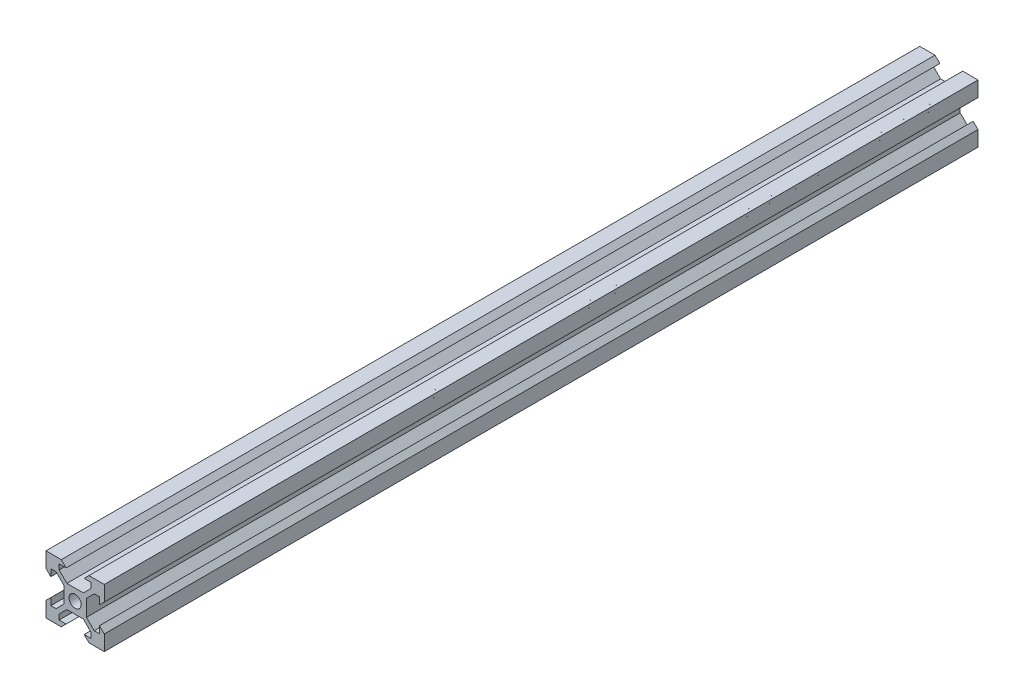
SolidWorks part; units mm, degrees
material "6061-T6 (SS)"
ref_plane "Front Plane" through (0, 0, 0) normal (0, 0, 1) x (1, 0, 0)
ref_plane "Top Plane" through (0, 0, 0) normal (0, 1, 0) x (1, 0, 0)
ref_plane "Right Plane" through (0, 0, 0) normal (1, 0, 0) x (0, 0, -1)
sketch "Sketch1" plane through (0, 0, 0) normal (0, 0, 1) x (1, 0, 0)
  line L0 (2.8343, 3.894) -> (5.5, 6.5588)
  line L1 (2.8343, -3.894) -> (-2.8343, -3.894)
  line L2 (3.8948, -2.8332) -> (3.8948, 2.8332)
  line L3 (2.8343, 3.894) -> (-2.8343, 3.894)
  line L4 (-3.8948, -2.8332) -> (-3.8948, 2.8332)
  line L5 (3.8994, -3.9006) -> (-3.8994, 3.9006) construction
  line L6 (3.9006, 3.8994) -> (-3.9006, -3.8994) construction
  line L7 (10, 4.747) -> (10, 9.9986)
  line L8 (5.5, 6.5588) -> (5.5, 8.3491)
  line L9 (5.5, 8.3491) -> (3.1, 8.3491)
  line L10 (3.1, 8.3491) -> (4.75, 9.9986)
  line L11 (4.75, 9.9986) -> (10, 9.9986)
  line L12 (8.35, 3.0975) -> (10, 4.747)
  line L13 (8.3507, 5.4975) -> (8.35, 3.0975)
  line L14 (6.5605, 5.498) -> (8.3507, 5.4975)
  line L15 (3.8948, 2.8332) -> (6.5605, 5.498)
  line L16 (0, -55) -> (0, 55) construction
  line L17 (-3.8948, 2.8332) -> (-6.5605, 5.498)
  line L18 (-6.5605, 5.498) -> (-8.3507, 5.4975)
  line L19 (-8.3507, 5.4975) -> (-8.35, 3.0975)
  line L20 (-8.35, 3.0975) -> (-10, 4.747)
  line L21 (-4.75, 9.9986) -> (-10, 9.9986)
  line L22 (-3.1, 8.3491) -> (-4.75, 9.9986)
  line L23 (-5.5, 8.3491) -> (-3.1, 8.3491)
  line L24 (-5.5, 6.5588) -> (-5.5, 8.3491)
  line L25 (-10, 4.747) -> (-10, 9.9986)
  line L26 (-2.8343, 3.894) -> (-5.5, 6.5588)
  line L27 (55, 0) -> (-55, 0) construction
  line L28 (3.8948, -2.8332) -> (6.5605, -5.498)
  line L29 (2.8343, -3.894) -> (5.5, -6.5588)
  line L30 (-3.8948, -2.8332) -> (-6.5605, -5.498)
  line L31 (-2.8343, -3.894) -> (-5.5, -6.5588)
  line L32 (-8.3507, -5.4975) -> (-8.35, -3.0975)
  line L33 (-8.35, -3.0975) -> (-10, -4.747)
  line L34 (8.3507, -5.4975) -> (8.35, -3.0975)
  line L35 (8.35, -3.0975) -> (10, -4.747)
  line L36 (-10, -4.747) -> (-10, -9.9986)
  line L37 (-5.5, -6.5588) -> (-5.5, -8.3491)
  line L38 (-5.5, -8.3491) -> (-3.1, -8.3491)
  line L39 (-3.1, -8.3491) -> (-4.75, -9.9986)
  line L40 (-4.75, -9.9986) -> (-10, -9.9986)
  line L41 (-6.5605, -5.498) -> (-8.3507, -5.4975)
  line L42 (6.5605, -5.498) -> (8.3507, -5.4975)
  line L43 (4.75, -9.9986) -> (10, -9.9986)
  line L44 (3.1, -8.3491) -> (4.75, -9.9986)
  line L45 (5.5, -8.3491) -> (3.1, -8.3491)
  line L46 (5.5, -6.5588) -> (5.5, -8.3491)
  line L47 (10, -4.747) -> (10, -9.9986)
  circle A0 centre (0, 0) radius 2.1
  point P0 (0, 0)
  dimension "D6" = 4.2
  dimension "D1" = 7.8
  dimension "D2" = 20
  dimension "D3" = 11
  dimension "D4" = 9.5
  dimension "D5" = 6.2
  dimension "D7" = 1.5
extrude "Boss-Extrude1" add sketch "Sketch1" along normal blind 300
